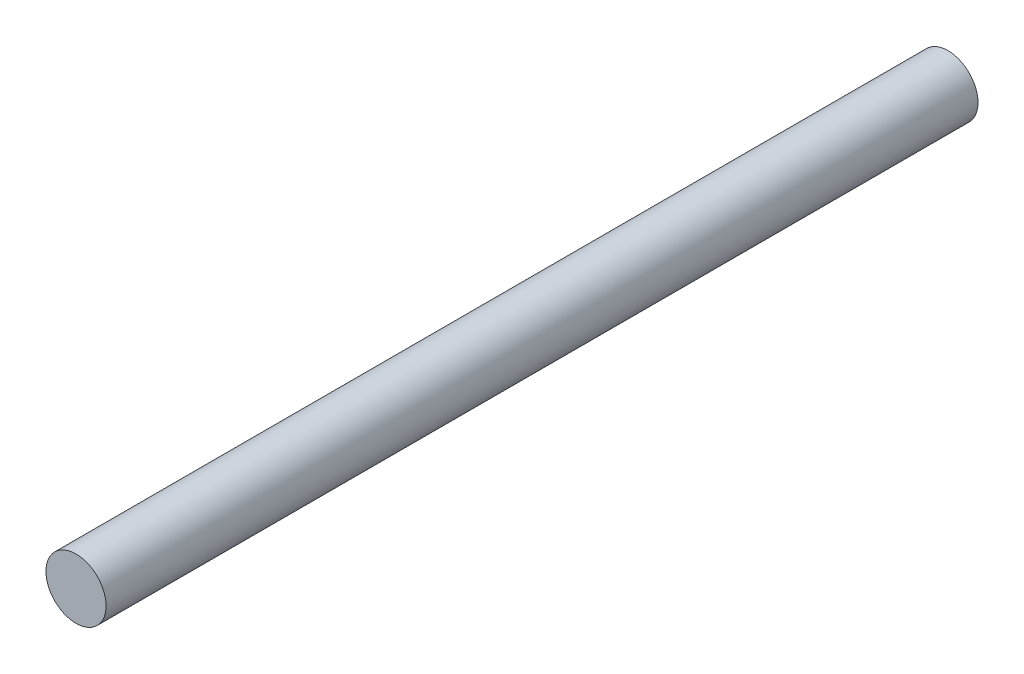
SolidWorks part; units mm, degrees
ref_plane "Front Plane" through (0, 0, 0) normal (0, 0, 1) x (1, 0, 0)
ref_plane "Top Plane" through (0, 0, 0) normal (0, 1, 0) x (1, 0, 0)
ref_plane "Right Plane" through (0, 0, 0) normal (1, 0, 0) x (0, 0, -1)
sketch "Sketch1" plane through (0, 0, 0) normal (0, 0, 1) x (1, 0, 0)
  circle A0 centre (0, 0) radius 0.5
  dimension "D1" = 1
extrude "Boss-Extrude1" add sketch "Sketch1" along normal blind 14.5
